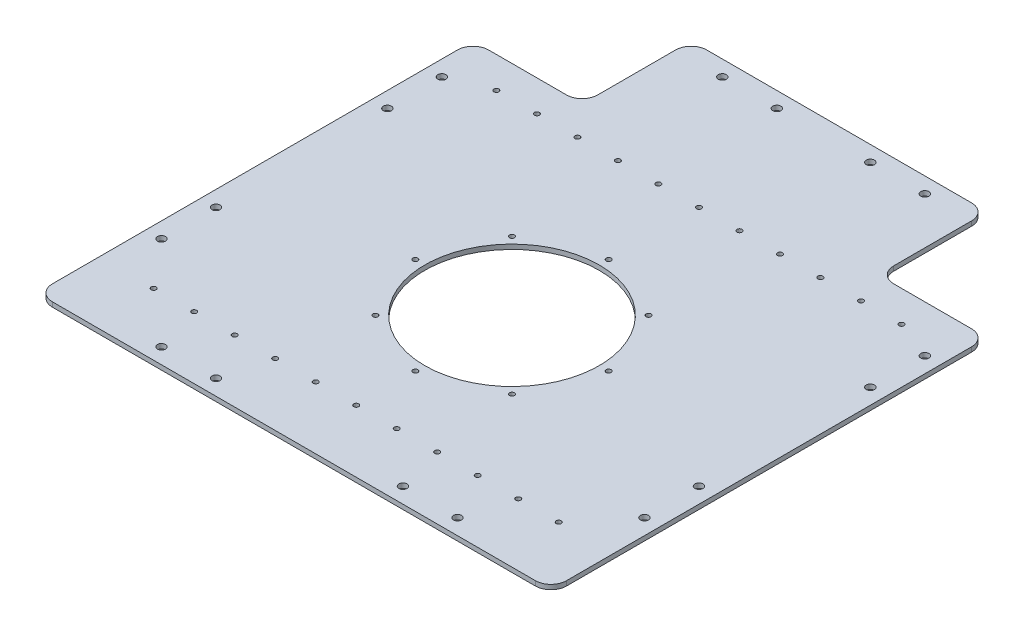
SolidWorks part; units mm, degrees
ref_plane "Front Plane" through (0, 0, 0) normal (0, 0, 1) x (1, 0, 0)
ref_plane "Top Plane" through (0, 0, 0) normal (0, 1, 0) x (1, 0, 0)
ref_plane "Right Plane" through (0, 0, 0) normal (1, 0, 0) x (0, 0, -1)
sketch "Sketch1" plane through (0, 0, 0) normal (0, 1, 0) x (1, 0, 0)
  line L0 (0, 140) -> (330, 140) construction
  line L1 (0, 0) -> (330, 0) construction
  line L2 (0, 0) -> (0, 350) construction
  line L3 (0, 350) -> (330, 350) construction
  line L4 (330, 0) -> (330, 350) construction
  line L5 (0, 0) -> (330, 0)
  line L6 (0, 0) -> (0, 280)
  line L7 (0, 280) -> (330, 280)
  line L8 (330, 0) -> (330, 280)
  line L9 (70, 280) -> (260, 280)
  line L10 (70, 280) -> (70, 350)
  line L11 (70, 350) -> (260, 350)
  line L12 (260, 280) -> (260, 350)
  circle A0 centre (165, 140) radius 56
  point P11 (165, 350)
  point P12 (165, 350)
  dimension "D5" = 112
  dimension "D1" = 330
  dimension "D2" = 350
  dimension "D3" = 70
  dimension "D4" = 70
extrude "Boss-Extrude1" add sketch "Sketch1" along normal blind 3 contours L5 L8 L7 L6 A0 | L7 L12 L11 L10
fillet "Fillet1" radius 10 8 edges at (0, 1.5, 0) (0, 1.5, -280) (70, 1.5, -280) (70, 1.5, -350) (260, 1.5, -350) (260, 1.5, -280) (330, 1.5, -280) (330, 1.5, 0)
sketch "Sketch2" plane through (0, 3, 0) normal (0, 1, 0) x (1, 0, 0)
  line L0 (80, 350) -> (250, 350) construction
  line L1 (0, 0) -> (330, 0) construction
  line L2 (0, 0) -> (0, 350) construction
  line L3 (0, 350) -> (330, 350) construction
  line L4 (330, 0) -> (330, 350) construction
  line L5 (330, 10) -> (330, 270) construction
  line L6 (20, 20) -> (20, 330) construction
  line L7 (20, 330) -> (310, 330) construction
  line L8 (310, 20) -> (310, 330) construction
  line L9 (20, 20) -> (310, 20) construction
  line L10 (10, 10) -> (10, 340) construction
  line L11 (10, 340) -> (320, 340) construction
  line L12 (320, 10) -> (320, 340) construction
  line L13 (10, 10) -> (320, 10) construction
  line L14 (10, 280) -> (60, 280) construction
  line L15 (270, 280) -> (320, 280) construction
  line L16 (70, 290) -> (70, 340) construction
  line L17 (260, 290) -> (260, 340) construction
  line L19 (35, 40) -> (295, 40) construction
  line L20 (35, 40) -> (35, 260) construction
  line L21 (35, 260) -> (295, 260) construction
  line L22 (295, 40) -> (295, 260) construction
  circle A0 centre (100, 340) radius 2.6
  circle A1 centre (230, 340) radius 2.6
  circle A2 centre (320, 250) radius 2.6
  circle A3 centre (320, 70) radius 2.6
  circle A4 centre (260, 10) radius 2.6
  circle A5 centre (10, 70) radius 2.6
  circle A6 centre (70, 10) radius 2.6
  circle A7 centre (10, 250) radius 2.6
  circle A8 centre (165, 140) radius 62 construction
  circle A9 centre (165, 140) radius 56 construction
  circle A10 centre (165, 202) radius 1.6
  circle A11 centre (208.8406, 183.8406) radius 1.6
  circle A12 centre (227, 140) radius 1.6
  circle A13 centre (208.8406, 96.1594) radius 1.6
  circle A14 centre (165, 78) radius 1.6
  circle A15 centre (121.1594, 96.1594) radius 1.6
  circle A16 centre (103, 140) radius 1.6
  circle A17 centre (121.1594, 183.8406) radius 1.6
  circle A18 centre (35, 260) radius 1.6
  circle A19 centre (61, 260) radius 1.6
  circle A20 centre (87, 260) radius 1.6
  circle A21 centre (113, 260) radius 1.6
  circle A22 centre (139, 260) radius 1.6
  circle A23 centre (165, 260) radius 1.6
  circle A24 centre (191, 260) radius 1.6
  circle A25 centre (217, 260) radius 1.6
  circle A26 centre (243, 260) radius 1.6
  circle A27 centre (269, 260) radius 1.6
  circle A28 centre (295, 260) radius 1.6
  circle A29 centre (35, 40) radius 1.6
  circle A30 centre (61, 40) radius 1.6
  circle A31 centre (87, 40) radius 1.6
  circle A32 centre (113, 40) radius 1.6
  circle A33 centre (139, 40) radius 1.6
  circle A34 centre (165, 40) radius 1.6
  circle A35 centre (191, 40) radius 1.6
  circle A36 centre (217, 40) radius 1.6
  circle A37 centre (243, 40) radius 1.6
  circle A38 centre (269, 40) radius 1.6
  circle A39 centre (295, 40) radius 1.6
  circle A40 centre (10, 215) radius 2.6
  circle A41 centre (10, 105) radius 2.6
  circle A42 centre (105, 10) radius 2.6
  circle A43 centre (225, 10) radius 2.6
  circle A44 centre (320, 105) radius 2.6
  circle A45 centre (320, 215) radius 2.6
  circle A46 centre (135, 340) radius 2.6
  circle A47 centre (195, 340) radius 2.6
  point P65 (165, 140)
  dimension "D4" = 5.2
  dimension "D5" = 70
  dimension "D8" = 70
  dimension "D9" = 30
  dimension "D11" = 30
  dimension "D12" = 6
  dimension "D13" = 3.2
  dimension "D19" = 3.2
  dimension "D21" = 3.2
  dimension "D3" = 30
  dimension "D6" = 70
  dimension "D7" = 70
  dimension "D10" = 30
  dimension "D15" = 20
  dimension "D16" = 20
  dimension "D17" = 35
  dimension "D18" = 35
  dimension "D23" = 35
  dimension "D24" = 35
  dimension "D25" = 35
  dimension "D26" = 35
  dimension "D27" = 35
  dimension "D28" = 35
  dimension "D29" = 35
  dimension "D30" = 35
  dimension "D1" = 20
  dimension "D2" = 10
  dimension "D20" = 11
  dimension "D22" = 11
  dimension "D14" = 8
extrude "Cut-Extrude1" cut sketch "Sketch2" against normal through all
